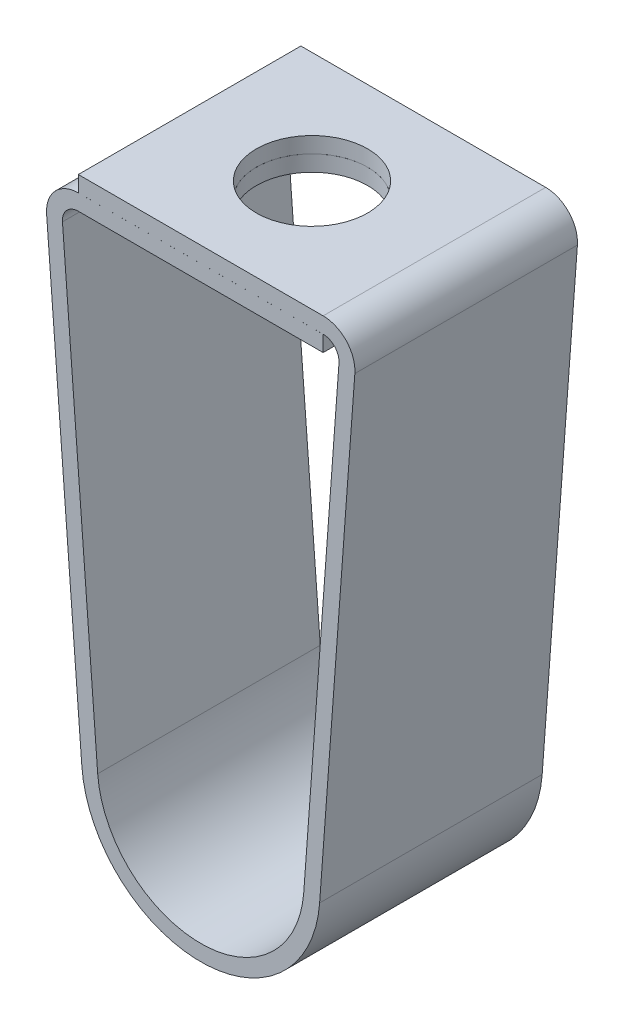
SolidWorks part; units mm, degrees
ref_plane "Front" through (0, 0, 0) normal (0, 0, 1) x (1, 0, 0)
ref_plane "Top" through (0, 0, 0) normal (0, 1, 0) x (1, 0, 0)
ref_plane "Right" through (0, 0, 0) normal (1, 0, 0) x (0, 0, -1)
sketch "Sketch1" plane through (0, 0, 0) normal (0, 0, 1) x (1, 0, 0)
  line L0 (-12.2237, 50.0697) -> (12.2238, 50.0697)
  line L1 (15.3901, 46.6605) -> (11.8738, -0.8783)
  line L2 (-12.2237, 50.0697) -> (-12.2238, 48.4823)
  line L3 (-12.2238, 48.4823) -> (12.2238, 48.4822)
  line L4 (13.8069, 46.7776) -> (10.2906, -0.7612)
  line L5 (-11.8715, -0.9085) -> (-15.3895, 45.0624)
  line L6 (-12.2238, 48.4797) -> (12.2238, 48.4797)
  line L7 (12.2238, 48.4797) -> (12.2238, 46.8922)
  line L8 (12.2238, 46.8922) -> (-12.2238, 46.8922)
  line L9 (-13.8066, 45.1836) -> (-10.2887, -0.7873)
  arc A0 (-10.2887, -0.7873) -> (10.2906, -0.7612) centre (0, 0) ccw
  arc A1 (-11.8715, -0.9085) -> (11.8738, -0.8783) centre (0, 0) ccw
  arc A2 (13.8069, 46.7776) -> (12.2238, 48.4822) centre (12.2238, 46.8947) ccw
  arc A3 (-13.8066, 45.1836) -> (-12.2238, 46.8922) centre (-12.2238, 45.3047) cw
  arc A4 (15.3901, 46.6605) -> (12.2238, 50.0697) centre (12.2238, 46.8947) ccw
  arc A5 (-15.3895, 45.0624) -> (-12.2238, 48.4797) centre (-12.2238, 45.3047) cw
  circle A6 centre (0, 48.4822) radius 5.5563 construction
  circle A7 centre (0, 48.4822) radius 12.2238 construction
  dimension "D4" = 1.5875
  dimension "D7" = 24.4475
  dimension "D5" = 0.0025
extrude "Boss-Extrude1" add sketch "Sketch1" along normal mid plane 22.225
sketch "Sketch2" plane through (0, 0, 0) normal (0, 1, 0) x (1, 0, 0)
  circle A0 centre (0, 0) radius 5.5562
  dimension "D1" = 11.1125
extrude "Cut-Extrude1" cut sketch "Sketch2" along normal through all
sketch "Ref1" plane through (0, 0, 0) normal (0, 0, 1) x (1, 0, 0)
  arc A0 (-10.2887, -0.7873) -> (10.2906, -0.7612) centre (0, 0) ccw construction
  arc A1 (10.2906, -0.7612) -> (-10.2887, -0.7873) centre (0, 0) ccw
equation "\"D7@Sketch1\" = \"Hole Dia@Sketch1\" * 2.2"
equation "\"D4@Sketch1\" = \"Thickness@Sketch1\""
equation "\"D1@Sketch2\" = \"Hole Dia@Sketch1\""
